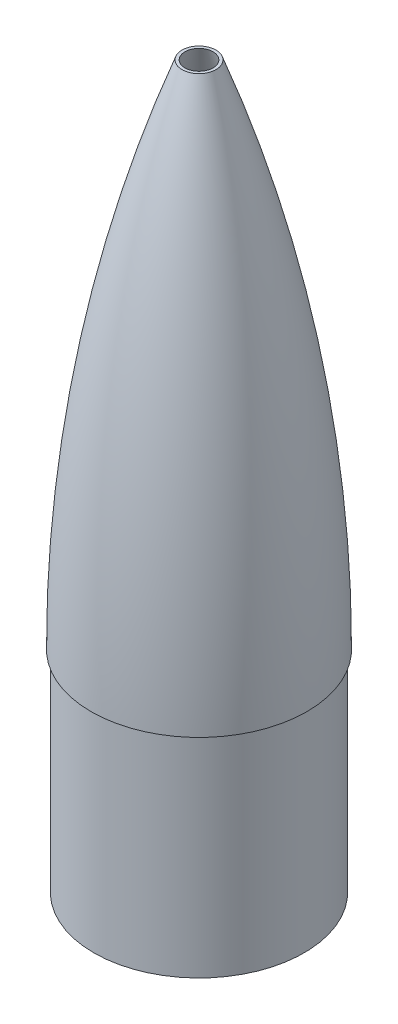
SolidWorks part; units mm, degrees
other "Markup1"
sketch "Sketch4" plane through (78.16, -154.2442, 78.16) normal (0.9651, -0.1718, 0.1975) x (-0.1686, -0.9851, -0.0334)
material "Thornel Mat VMA"
ref_plane "Front Plane" through (0, 0, 0) normal (0, 0, 1) x (1, 0, 0)
ref_plane "Top Plane" through (0, 0, 0) normal (0, 1, 0) x (1, 0, 0)
ref_plane "Right Plane" through (0, 0, 0) normal (1, 0, 0) x (0, 0, -1)
sketch "Sketch1" plane through (0, 0, 0) normal (0, 0, 1) x (1, 0, 0)
  line L3 (0, 0) -> (0, 398.8705) construction
  line L6 (0, 400) -> (0, 401.8534)
  line L8 (78.2, 0) -> (76.2, 0)
  line L9 (0, 400) -> (0, 396.4892)
  line L10 (76.2, 0) -> (-993.4203, 0) construction
  line L11 (0, 411.0234) -> (0, 614.1078) construction
  arc A0 (76.2, 0) -> (0, 396.4892) centre (-993.4203, 0) ccw
  arc A1 (78.2, 0) -> (0, 401.8534) centre (-993.4203, 0) ccw
  circle A2 centre (-993.4203, 0) radius 1069.6203 construction
  circle A3 centre (-993.4203, 0) radius 1071.6203 construction
  point P7 (0, 401.3589)
  point P11 (0, 400)
  point P12 (0, 0)
  point P19 (0, 0)
  dimension "D1" = 400
  dimension "D2" = 3.5108
  dimension "D3" = 2
  dimension "D4" = 76.2
revolve "Revolve3" add sketch "Sketch1" angle 360 about L6
sketch "Sketch2" plane through (0, 0, 0) normal (0, 1, 0) x (1, 0, 0)
  circle A3 centre (0, 0) radius 76.2 construction
  circle A4 centre (0, 0) radius 76.2
  circle A5 centre (0, 0) radius 74.2
  dimension "D1" = 2
extrude "Boss-Extrude1" add sketch "Sketch2" against normal blind 152.4 and the other way blind 10
ref_plane "Plane2" through (0, 400, 0) normal (0, -1, 0) x (-1, 0, 0)
ref_plane "Plane4" through (0, 370, 0) normal (0, -1, 0) x (-1, 0, 0)
sketch "Sketch6" plane through (0, 370, 0) normal (0, -1, 0) x (-1, 0, 0)
  circle A0 centre (0, 0) radius 45.0274
extrude "Cut-Extrude1" cut sketch "Sketch6" against normal blind 40
ref_plane "Plane3" through (0, -6.4, 0) normal (0, -1, 0) x (-1, 0, 0)
sketch "Sketch5" plane through (0, -6.4, 0) normal (0, -1, 0) x (-1, 0, 0)
  circle A0 centre (0, 0) radius 73.2
  circle A1 centre (0, 0) radius 73.2
